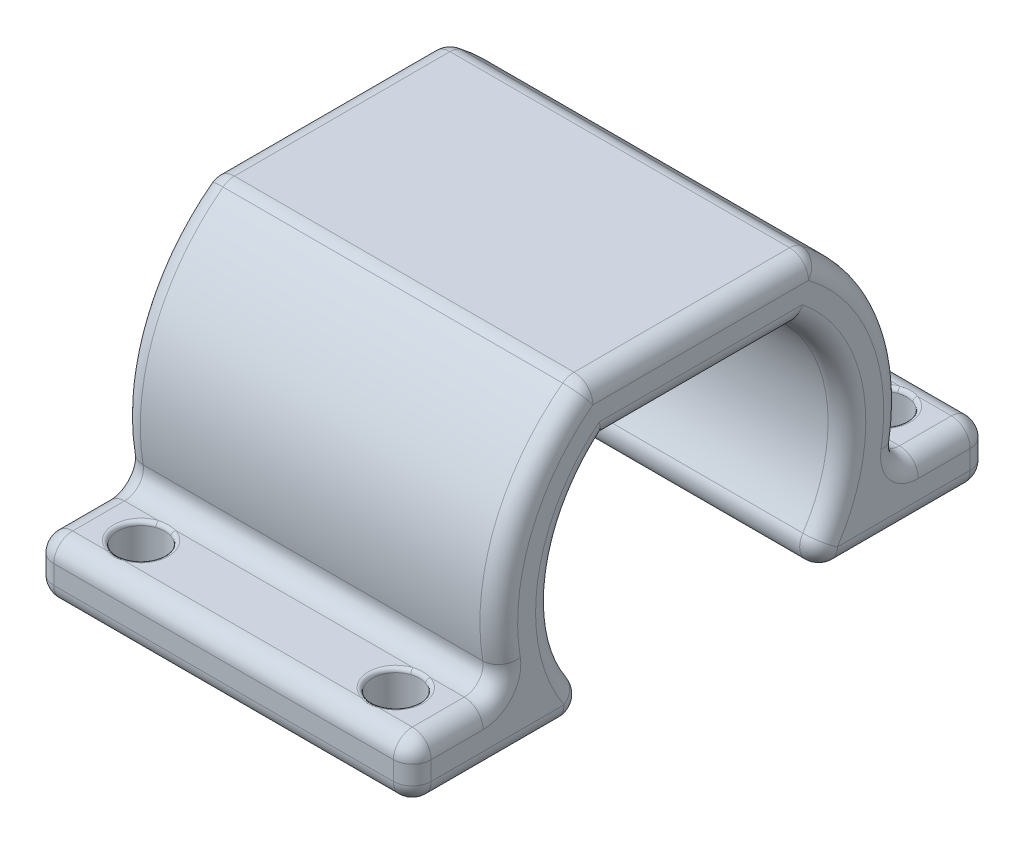
SolidWorks part; units mm, degrees
ref_plane "Спереди" through (0, 0, 0) normal (0, 0, 1) x (1, 0, 0)
ref_plane "Сверху" through (0, 0, 0) normal (0, 1, 0) x (1, 0, 0)
ref_plane "Справа" through (0, 0, 0) normal (1, 0, 0) x (0, 0, -1)
sketch "Эскиз1" plane through (0, 0, 0) normal (1, 0, 0) x (0, 0, -1)
  line L1 (15.2837, -3) -> (10.2837, -3)
  line L4 (-5.0751, -6) -> (-15.2837, -6)
  line L6 (0, 6) -> (0, -6) construction
  line L8 (-6.0368, 9) -> (6.0368, 9)
  line L11 (-15.2837, -3) -> (-10.2837, -3)
  line L12 (-15.2837, -3) -> (-15.2837, -6)
  line L14 (-5.0189, 6.05) -> (5.0189, 6.05)
  line L17 (15.2837, -3) -> (15.2837, -6)
  line L18 (5.0751, -6) -> (15.2837, -6)
  arc A2 (6.0368, 9) -> (10.2837, -3) centre (-0.3167, 0) cw
  arc A3 (-6.0368, 9) -> (-10.2837, -3) centre (0.3167, 0) ccw
  arc A4 (-5.0189, 6.05) -> (-5.0751, -6) centre (0.3167, 0) ccw
  arc A7 (5.0189, 6.05) -> (5.0751, -6) centre (-0.3167, 0) cw
  point P5 (5, 6)
  point P12 (-5, -6)
  point P13 (5, -6)
  point P15 (-0.3167, 0)
  point P19 (6.0368, -9)
  point P20 (-6.0368, -9)
  point P25 (0, -6)
  point P27 (-5.0332, -6.0374)
  point P30 (5.0332, -6.0374)
  dimension "D1" = 5
  dimension "D5" = 3
extrude "Бобышка-Вытянуть1" add sketch "Эскиз1" along normal blind 20
fillet "Скругление1" radius 1 2 edges at (10, -6, 5.0751) (10, -6, -5.0751)
fillet "Скругление2" radius 1 36 edges at (0, 6.05, 0) (0, 1.0615, -7.6799) (0, -5.4736, -6.3659) (0, -6, -11.2652) (0, -3, -12.7837) (0, 3.6754, -10.0688) (0, 9, 0) (0, 3.6754, 10.0688) (0, -3, 12.7837) (0, -6, 11.2652) (0, -5.4736, 6.3659) (0, 1.0615, 7.6799) (10, -3, 15.2837) (10, -6, 15.2837) (0, -4.5, 15.2837) (10, -6, -15.2837) (10, -3, -15.2837) (0, -4.5, -15.2837) (20, -4.5, 15.2837) (20, -3, 12.7837) (20, 3.6754, 10.0688) (20, 9, 0) (20, 3.6754, -10.0688) (20, -3, -12.7837) (20, -4.5, -15.2837) (20, -6, -11.2652) (20, -5.4736, -6.3659) (20, 1.0615, -7.6799) (20, 6.05, 0) (20, 1.0615, 7.6799) (20, -5.4736, 6.3659) (20, -6, 11.2652) (10, -3, -10.2837) (10, -3, 10.2837) (10, 9, -6.0368) (10, 9, 6.0368)
sketch "Эскиз2" plane through (0, -3, 0) normal (0, 1, 0) x (1, 0, 0)
  line L0 (1, 14.2837) -> (1, 11.5324) construction
  line L1 (3.25, 14.2837) -> (3.25, 11.5324) construction
  line L2 (5.5, 14.2837) -> (5.5, 11.5324) construction
  line L3 (7.75, 14.2837) -> (7.75, 11.5324) construction
  line L4 (10, 14.2837) -> (10, 11.5324) construction
  line L5 (12.25, 14.2837) -> (12.25, 11.5324) construction
  line L6 (14.5, 14.2837) -> (14.5, 11.5324) construction
  line L7 (16.75, 14.2837) -> (16.75, 11.5324) construction
  line L8 (19, 14.2837) -> (19, 11.5324) construction
  line L9 (1, 14.2837) -> (3.25, 14.2837) construction
  line L10 (0, 0) -> (20, 0) construction
  line L11 (20, 5.7111) -> (20, -5.7111) construction
  line L12 (3.25, 12.908) -> (16.75, 12.908) construction
  circle A0 centre (3.25, 12.908) radius 1.25
  circle A1 centre (16.75, 12.908) radius 1.25
  circle A2 centre (3.25, -12.908) radius 1.25
  circle A3 centre (16.75, -12.908) radius 1.25
  dimension "D3" = 2
  dimension "D2" = 2.25
  dimension "D4" = 13.5
  dimension "D1" = 9
extrude "Вырез-Вытянуть1" cut sketch "Эскиз2" against normal through all
fillet "Скругление3" radius 0.2 4 edges at (16.75, -3, 11.658) (3.25, -3, 11.658) (16.75, -3, -11.658) (3.25, -3, -11.658)
